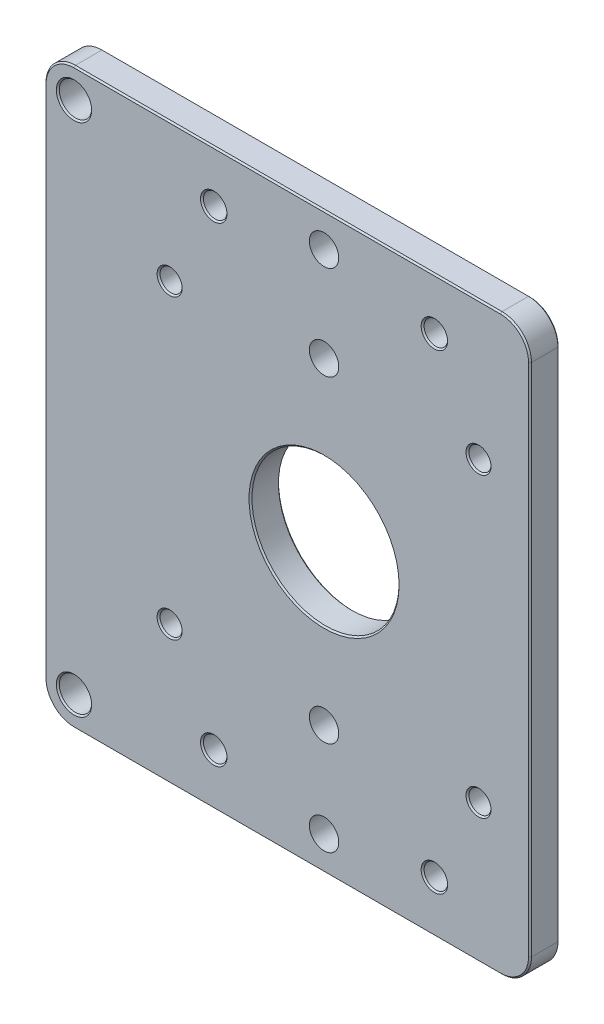
SolidWorks part; units mm, degrees
material "2A12"
ref_plane "前视基准面" through (0, 0, 0) normal (0, 0, 1) x (1, 0, 0)
ref_plane "上视基准面" through (0, 0, 0) normal (0, 1, 0) x (1, 0, 0)
ref_plane "右视基准面" through (0, 0, 0) normal (1, 0, 0) x (0, 0, -1)
sketch "草图2" plane through (0, 0, 0) normal (0, 0, 1) x (1, 0, 0)
  line L0 (0, 19.5) -> (0, -19.5) construction
  line L1 (-19, 19.5) -> (19, 19.5)
  line L2 (-19, 19.5) -> (-19, -19.5)
  line L3 (-19, -19.5) -> (19, -19.5)
  line L4 (19, 19.5) -> (19, -19.5)
  dimension "D1" = 38
  dimension "D2" = 39
extrude "拉伸1" add sketch "草图2" along normal blind 2
sketch "草图3" plane through (0, 0, 2) normal (0, 0, 1) x (1, 0, 0)
  line L0 (-14, 16.5) -> (-14, -16.5) construction
  line L1 (0, 0) -> (-14, 0) construction
  line L2 (-19, 19.5) -> (-19, -19.5) construction
  circle A0 centre (-14, 16.5) radius 1.75
  circle A1 centre (-14, -16.5) radius 1.75
  dimension "D2" = 3.5
  dimension "D1" = 33
  dimension "D3" = 5
fillet "圆角1" [suppressed] radius 20
chamfer "倒角1" [suppressed] distance 22 angle 30
chamfer "倒角2" [suppressed] distance 22 angle 30
fillet "圆角2" [suppressed] radius 10
chamfer "倒角3" distance 1 angle 45 2 edges at (-19, -19.5, 1) (-19, 19.5, 1)
sketch "草图4" plane through (0, 0, 2) normal (0, 0, 1) x (1, 0, 0)
  line L0 (8.205, 5.2066) -> (-4.205, -5.2066) construction
  line L1 (2, 0) -> (2, 7.25) construction
  line L2 (-3.5538, 4.6602) -> (7.5538, -4.6602) construction
  line L3 (2, 0) -> (19, 0) construction
  line L4 (-19, 18.5) -> (-19, -18.5) construction
  line L5 (19, -19.5) -> (19, 19.5) construction
  circle A0 centre (2, 0) radius 8.1 construction
  circle A1 centre (2, 0) radius 7.25 construction
  dimension "D1" = 16.2
  dimension "D2" = 14.5
  dimension "D3" = 50
  dimension "D4" = 50
  dimension "D5" = 21
hole_wizard "M1.6 螺纹孔1" [suppressed] positions "3D草图2" profile "草图6" tap size "M1.6" standard "GB"
sketch3d "3D草图2"
  point P3 (13.145, 5.2066, 2)
  point P6 (12.4938, -4.6602, 2)
  point P9 (0.735, -5.2066, 2)
  point P12 (1.3862, 4.6602, 2)
sketch "草图6" plane through (13.145, 5.2066, 2) normal (1, 0, 0) x (0, -1, 0)
  line L0 (0, 0) -> (0, 4.6255)
  line L1 (0, 4.6255) -> (0.625, 4.25)
  line L2 (0.625, 4.25) -> (0.625, 0)
  line L5 (0.625, 0) -> (0, 0)
  line L10 (0, 4.6255) -> (-0.625, 4.25) construction
  line L11 (0, -6.35) -> (0, 107.95) construction
  dimension "螺纹孔钻头直径" = 1.25
  dimension "螺纹孔钻头深度" = 4.25
  dimension "导头角度" = 118
cosmetic thread "Hole Thread1" [suppressed] parameters "D1"=2, "D2"=1.6
cosmetic thread "Hole Thread2" [suppressed] parameters "D1"=2, "D2"=1.6
cosmetic thread "Hole Thread3" [suppressed] parameters "D1"=2, "D2"=1.6
cosmetic thread "Hole Thread4" [suppressed] parameters "D1"=2, "D2"=1.6
sketch "草图7" plane through (0, 0, 2) normal (0, 0, 1) x (1, 0, 0)
  line L0 (-3, 0) -> (2, 0) construction
  circle A0 centre (2, 0) radius 5
  dimension "D1" = 10
extrude "拉伸3" cut sketch "草图7" against normal blind 10
sketch "草图8" plane through (0, 0, 2) normal (0, 0, 1) x (1, 0, 0)
  line L0 (19, 19.5) -> (-18, 19.5) construction
  line L1 (-17, 19.5) -> (-19, 19.5)
  line L2 (-17, 19.5) -> (-17, -19.5)
  line L3 (-17, -19.5) -> (-19, -19.5)
  line L4 (-19, 19.5) -> (-19, -19.5)
  line L5 (-18, -19.5) -> (19, -19.5) construction
  line L6 (-19, 18.5) -> (-19, -18.5) construction
  dimension "D1" = 2
extrude "拉伸4" cut sketch "草图8" against normal blind 10
chamfer "倒角4" [suppressed] distance 1.5 angle 45
fillet "圆角3" radius 2 2 edges at (-17, -19.5, 1) (-17, 19.5, 1)
sketch "Sketch1" plane through (0, 0, 2) normal (0, 0, 1) x (1, 0, 0)
  line L0 (2, 0) -> (19, 0)
  line L1 (19, -19.5) -> (19, 19.5) construction
  line L2 (7.7569, 7.557) -> (-3.7569, -7.557)
  line L3 (-3.7569, 7.557) -> (7.7569, -7.557)
  dimension "D1" = 52.7
  dimension "D2" = 19
  dimension "D3" = 52.7
hole_wizard "M2.5 Tapped Hole1" [suppressed] positions "3DSketch1" profile "Sketch2" tap size "M2.5" standard "GB"
sketch3d "3DSketch1"
  point P0 (-3.7569, -7.557, 2)
  point P3 (7.7569, 7.557, 2)
  point P7 (-3.7569, 7.557, 2)
  point P10 (7.7569, -7.557, 2)
sketch "Sketch2" plane through (-3.7569, -7.557, 2) normal (1, 0, 0) x (0, -1, 0)
  line L0 (0, 0) -> (0, 7.8659)
  line L1 (0, 7.8659) -> (1.025, 7.25)
  line L2 (1.025, 7.25) -> (1.025, 0)
  line L5 (1.025, 0) -> (0, 0)
  line L10 (0, 7.8659) -> (-1.025, 7.25) construction
  line L11 (0, -6.35) -> (0, 107.95) construction
  dimension "Tap Drill Dia." = 2.05
  dimension "Tap Drill Depth" = 7.25
  dimension "Drill Angle" = 118
cosmetic thread "Hole Thread5" [suppressed] parameters "D1"=2, "D2"=2.5
cosmetic thread "Hole Thread6" [suppressed] parameters "D1"=2, "D2"=2.5
cosmetic thread "Hole Thread7" [suppressed] parameters "D1"=2, "D2"=2.5
cosmetic thread "Hole Thread8" [suppressed] parameters "D1"=2, "D2"=2.5
fillet "Fillet1" [suppressed] radius 3
sketch "Sketch3" [suppressed] plane through (0, 0, 2) normal (0, 0, 1) x (1, 0, 0)
  line L1 (19, 19.5) -> (15, 19.5)
  line L2 (19, 19.5) -> (19, 9.5)
  line L3 (19, 9.5) -> (15, 9.5)
  line L4 (15, 19.5) -> (15, 9.5)
  line L5 (19, -19.5) -> (15, -19.5)
  line L6 (19, -19.5) -> (19, -9.5)
  line L7 (19, -9.5) -> (15, -9.5)
  line L8 (15, -19.5) -> (15, -9.5)
  dimension "D1" = 10
  dimension "D2" = 4
extrude "Extrude1" [suppressed] cut sketch "Sketch3" against normal blind 10
chamfer "Chamfer1" [suppressed] distance 5 angle 45
fillet "Fillet2" [suppressed] radius 2.5
fillet "Fillet3" [suppressed] radius 2.5
fillet "Fillet4" [suppressed] radius 2.5
chamfer "Chamfer2" [suppressed] distance 4 angle 45
sketch "草图9" plane through (0, 0, 2) normal (0, 0, 1) x (1, 0, 0)
  circle A0 centre (-15, 17.5) radius 2
  arc A2 (-15, 19.5) -> (-17, 17.5) centre (-15, 17.5) ccw construction
  circle A3 centre (-15, -17.5) radius 2
  arc A4 (-17, -17.5) -> (-15, -19.5) centre (-15, -17.5) ccw construction
extrude "凸台-拉伸1" add sketch "草图9" along normal blind 23
mirror "镜向1" about plane through (0, 0, 0) normal (0, 1, 0) of "凸台-拉伸1"
fillet "圆角4" [suppressed] radius 1.5
sketch "草图10" plane through (0, 0, 0) normal (0, 0, -1) x (-1, 0, 0)
  line L0 (15, -19.5) -> (-19, -19.5) construction
  line L1 (-19, 19.5) -> (-16, 19.5)
  line L2 (-19, 19.5) -> (-19, -19.5)
  line L3 (-19, -19.5) -> (-16, -19.5)
  line L4 (-16, 19.5) -> (-16, -19.5)
  dimension "D1" = 3
extrude "切除-拉伸1" cut sketch "草图10" against normal blind 10
fillet "圆角5" radius 2 2 edges at (16, -19.5, 1) (16, 19.5, 1)
chamfer "倒角5" distance 0.5 angle 45 2 edges at (-13, -17.5, 25) (-13, 17.5, 25)
sketch "草图20" plane through (0, 0, 0) normal (0, 0, -1) x (-1, 0, 0)
  line L0 (3.7569, 7.557) -> (-7.7569, -7.557) construction
  line L1 (-9.5, -16) -> (5.5, -16)
  line L2 (-9.5, -16) -> (-9.5, 16)
  line L3 (-9.5, 16) -> (5.5, 16)
  line L4 (5.5, -16) -> (5.5, 16)
  line L5 (-9.5, -16) -> (5.5, 16) construction
  line L6 (-9.5, 16) -> (5.5, -16) construction
  point P0 (-2, 0)
  dimension "D1" = 32
  dimension "D2" = 15
hole_wizard "M2 螺纹孔1" positions "3D草图7" profile "草图21" tap size "M2" standard "GB" end condition up to next
sketch3d "3D草图7"
  point P0 (9.5, 16, 0)
  point P3 (-5.5, 16, 0)
  point P6 (9.5, -16, 0)
  point P9 (-5.5, -16, 0)
sketch "草图21" plane through (9.5, 16, 0) normal (1, 0, 0) x (0, 1, 0)
  line L0 (0, 0) -> (0, 2)
  line L1 (0, 2) -> (0.8, 2)
  line L2 (0.8, 2) -> (0.8, 0)
  line L5 (0.8, 0) -> (0, 0)
  line L11 (0, -6.35) -> (0, 107.95) construction
  dimension "通孔螺纹孔钻头直径" = 1.6
  dimension "通孔螺纹孔钻头深度" = 2
cosmetic thread "孔螺蚊线7" parameters "D2"=2
cosmetic thread "孔螺蚊线8" parameters "D2"=2
cosmetic thread "孔螺蚊线9" parameters "D2"=2
cosmetic thread "孔螺蚊线10" parameters "D2"=2
hole_wizard "Ø2.2 (2.2) 直径孔1" positions "3D草图8" profile "草图22" hole size "Ø2.2" standard "GB"
sketch3d "3D草图8"
  line L0 (-15, 17.5, 24.5) -> (-15, 17.5, 25) construction
  line L1 (-15, -17.5, 24.5) -> (-15, -17.5, 25) construction
  point P0 (-15, 17.5, 25)
  point P4 (-15, -17.5, 25)
sketch "草图22" plane through (-15, 17.5, 25) normal (1, 0, 0) x (0, -1, 0)
  line L0 (0, 0) -> (0, 114.6609)
  line L1 (0, 114.6609) -> (1.1, 114)
  line L2 (1.1, 114) -> (1.1, 0)
  line L5 (1.1, 0) -> (0, 0)
  line L10 (0, 114.6609) -> (-1.1, 114) construction
  line L11 (0, -6.35) -> (0, 107.95) construction
  dimension "孔直径" = 2.2
  dimension "孔深度" = 114
  dimension "导头角度" = 118
sketch "草图23" plane through (0, 0, 0) normal (0, 0, -1) x (-1, 0, 0)
  line L0 (-2, 16.5) -> (-2, 8.5) construction
  line L1 (-0.5, 16.5) -> (-0.5, 8.5)
  line L2 (-3.5, 16.5) -> (-3.5, 8.5)
  line L3 (-14, 19.5) -> (15, 19.5) construction
  line L4 (-16, -17.5) -> (-16, 17.5) construction
  arc A0 (-0.5, 16.5) -> (-3.5, 16.5) centre (-2, 16.5) ccw
  arc A1 (-3.5, 8.5) -> (-0.5, 8.5) centre (-2, 8.5) ccw
  point P2 (-2, 12.5)
  dimension "D1" = 1.5
  dimension "D2" = 3
  dimension "D3" = 14
  dimension "D4" = 8
extrude "切除-拉伸2" [suppressed] cut sketch "草图23" against normal blind 10
mirror "镜向2" [suppressed] about plane through (0, 0, 0) normal (0, 1, 0)
sketch "草图24" plane through (0, 0, 2) normal (0, 0, 1) x (1, 0, 0)
  line L1 (34.0206, -28.4208) -> (-34.0206, -28.4208)
  line L2 (34.0206, -28.4208) -> (34.0206, 28.4208)
  line L3 (34.0206, 28.4208) -> (-34.0206, 28.4208)
  line L4 (-34.0206, -28.4208) -> (-34.0206, 28.4208)
  line L5 (34.0206, -28.4208) -> (-34.0206, 28.4208) construction
  line L6 (34.0206, 28.4208) -> (-34.0206, -28.4208) construction
  point P0 (0, 0)
extrude "切除-拉伸3" cut sketch "草图24" along normal blind 95
sketch "草图26" plane through (0, 0, 0) normal (0, 0, -1) x (-1, 0, 0)
  line L1 (8.5, -10.1) -> (-12.5, -10.1)
  line L2 (8.5, -10.1) -> (8.5, 10.1)
  line L3 (8.5, 10.1) -> (-12.5, 10.1)
  line L4 (-12.5, -10.1) -> (-12.5, 10.1)
  line L5 (8.5, -10.1) -> (-12.5, 10.1) construction
  line L6 (8.5, 10.1) -> (-12.5, -10.1) construction
  point P0 (-2, 0)
  dimension "D1" = 10.1
  dimension "D2" = 21
hole_wizard "Ø1.5 (1.5) 直径孔1" positions "3D草图9" profile "草图27" hole size "Ø1.5" standard "GB"
sketch3d "3D草图9"
  point P0 (12.5, 10.1, 0)
  point P3 (-8.5, 10.1, 0)
  point P6 (-8.5, -10.1, 0)
  point P9 (12.5, -10.1, 0)
sketch "草图27" plane through (12.5, 10.1, 0) normal (1, 0, 0) x (0, 1, 0)
  line L0 (0, 0) -> (0, 43.4506)
  line L1 (0, 43.4506) -> (0.75, 43)
  line L2 (0.75, 43) -> (0.75, 0)
  line L5 (0.75, 0) -> (0, 0)
  line L10 (0, 43.4506) -> (-0.75, 43) construction
  line L11 (0, -6.35) -> (0, 107.95) construction
  dimension "孔直径" = 1.5
  dimension "孔深度" = 43
  dimension "导头角度" = 118
chamfer "倒角6" distance 0.1 angle 45 19 edges at (-13.9, 17.5, 0) (-13.9, -17.5, 0) (8.7, 16, 0) (-6.3, 16, 0) (8.7, -16, 0) (15.4142, 18.9142, 0) (-0.5, 19.5, 0) (-16.4142, 18.9142, 0) (-17, 0, 0) (-16.4142, -18.9142, 0) (-0.5, -19.5, 0) (15.4142, -18.9142, 0) (16, 0, 0) (7, 0, 0) (-6.3, -16, 0) (11.75, -10.1, 0) (-9.25, -10.1, 0) (-9.25, 10.1, 0) (11.75, 10.1, 0)
chamfer "倒角7" distance 0.1 angle 45 19 edges at (-13.9, -17.5, 2) (-13.9, 17.5, 2) (10.3, 16, 2) (-4.7, 16, 2) (10.3, -16, 2) (-4.7, -16, 2) (-16.4142, -18.9142, 2) (15.4142, 18.9142, 2) (16, 0, 2) (15.4142, -18.9142, 2) (-0.5, -19.5, 2) (7, 0, 2) (13.25, -10.1, 2) (-7.75, -10.1, 2) (-7.75, 10.1, 2) (13.25, 10.1, 2)
sketch "草图28" plane through (0, 0, 0) normal (0, 0, -1) x (-1, 0, 0)
  line L0 (-2, 17.2) -> (-2, 10.8) construction
  circle A0 centre (-2, 0) radius 10.8
  circle A1 centre (-2, 0) radius 17.2
  dimension "D1" = 21.6
  dimension "D2" = 6.4
hole_wizard "Ø2.0 (2) 直径孔1" positions "3D草图10" profile "草图29" hole size "Ø2.0" standard "GB" end condition through all
sketch3d "3D草图10"
  point P0 (2, 10.8, 0)
  point P3 (2, 17.2, 0)
sketch "草图29" plane through (2, 10.8, 0) normal (1, 0, 0) x (0, 1, 0)
  line L0 (0, 0) -> (0, 2)
  line L1 (0, 2) -> (1, 2)
  line L2 (1, 2) -> (1, 0)
  line L5 (1, 0) -> (0, 0)
  line L11 (0, -6.35) -> (0, 107.95) construction
  dimension "通孔孔直径" = 2
  dimension "通孔孔深度" = 2
mirror "镜向3" about plane through (0, 0, 0) normal (0, 1, 0) of "Ø2.0 (2) 直径孔1"
